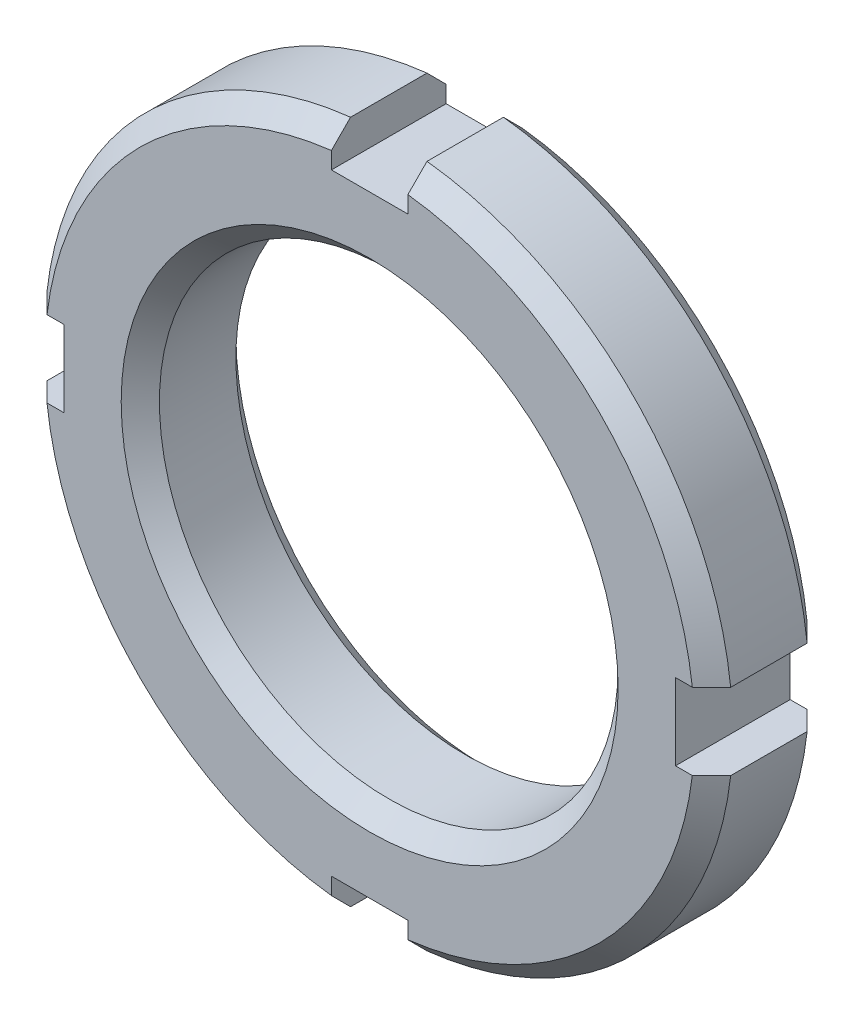
SolidWorks part; units mm, degrees
ref_plane "Спереди" through (0, 0, 0) normal (0, 0, 1) x (1, 0, 0)
ref_plane "Сверху" through (0, 0, 0) normal (0, 1, 0) x (1, 0, 0)
ref_plane "Справа" through (0, 0, 0) normal (1, 0, 0) x (0, 0, -1)
sketch "Эскиз1" plane through (0, 0, 0) normal (0, 0, 1) x (1, 0, 0)
  circle A0 centre (0, 0) radius 9
  circle A1 centre (0, 0) radius 6
  dimension "D1" = 12
  dimension "D2" = 18
extrude "Бобышка-Вытянуть1" add sketch "Эскиз1" along normal blind 3
chamfer "Фаска1" distance 0.5 angle 45 4 edges at (6, 0, 0) (9, 0, 0) (6, 0, 3) (9, 0, 3)
sketch "Эскиз2" plane through (0, 0, 3) normal (0, 0, 1) x (1, 0, 0)
  line L0 (0, 0) -> (0, 9) construction
  line L2 (1, 10) -> (-1, 10)
  line L3 (1, 10) -> (1, 8)
  line L4 (1, 8) -> (-1, 8)
  line L5 (-1, 10) -> (-1, 8)
  line L6 (1, 10) -> (-1, 8) construction
  line L7 (1, 8) -> (-1, 10) construction
  circle A0 centre (0, 0) radius 9 construction
  dimension "D1" = 2
  dimension "D2" = 2
extrude "Вырез-Вытянуть1" cut sketch "Эскиз2" against normal through all
pattern_circular "Круговой массив1" count 4 over 360 about axis through (0, 0, 0) along (0, 0, 1) of "Вырез-Вытянуть1"
